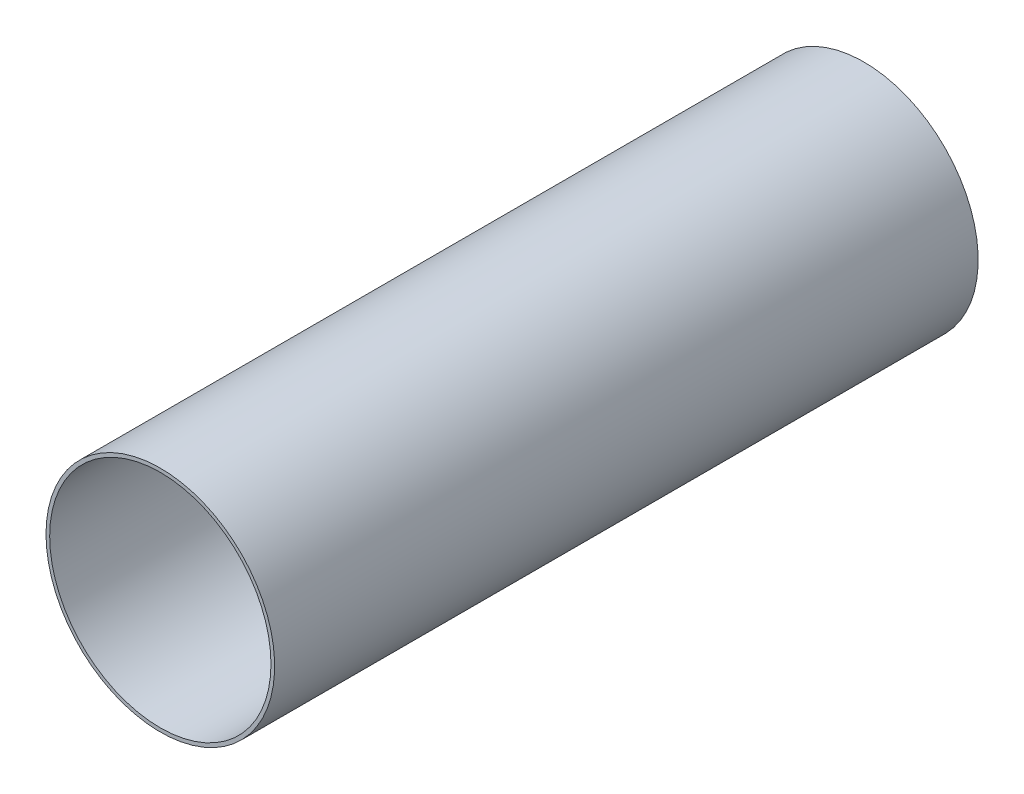
SolidWorks part; units mm, degrees
material "Thornel Mat VMA"
ref_plane "Front Plane" through (0, 0, 0) normal (0, 0, 1) x (1, 0, 0)
ref_plane "Top Plane" through (0, 0, 0) normal (0, 1, 0) x (1, 0, 0)
ref_plane "Right Plane" through (0, 0, 0) normal (1, 0, 0) x (0, 0, -1)
sketch "Sketch1" plane through (0, 0, 0) normal (0, 0, 1) x (1, 0, 0)
  circle A0 centre (0, 0) radius 49.53
  circle A1 centre (0, 0) radius 47.9425
  dimension "D1" = 99.06
  dimension "D2" = 1.5875
extrude "Boss-Extrude1" add sketch "Sketch1" along normal blind 304.8
